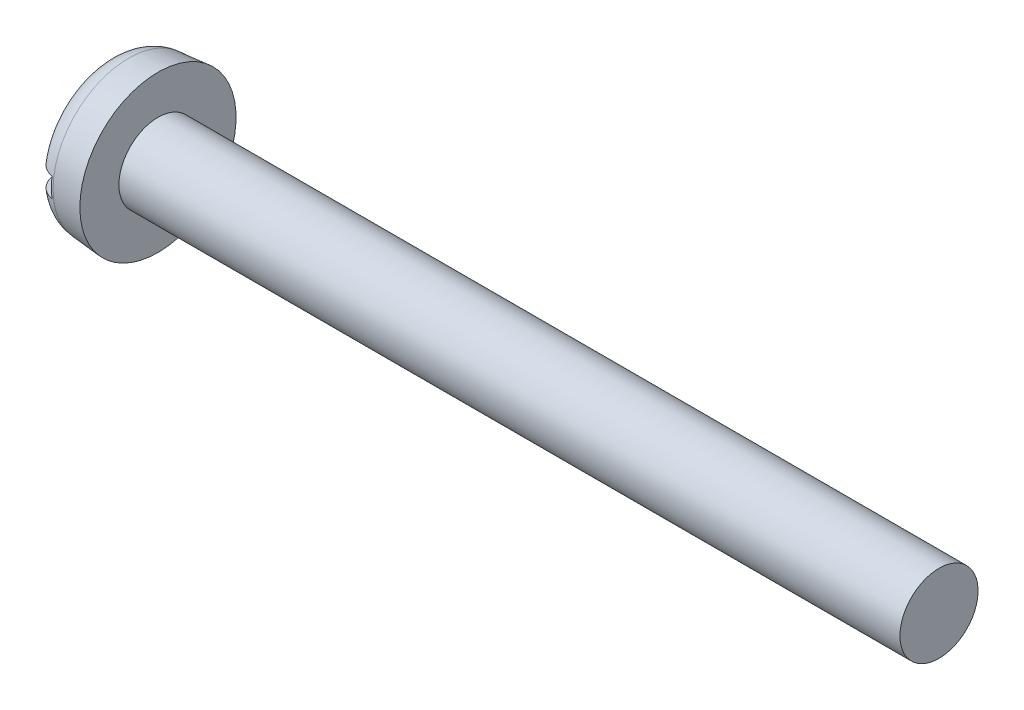
SolidWorks part; units mm, degrees
ref_plane "Plane1" through (0, 0, 0) normal (0, 0, 1) x (1, 0, 0)
ref_plane "Plane2" through (0, 0, 0) normal (0, 1, 0) x (1, 0, 0)
ref_plane "Plane3" through (0, 0, 0) normal (1, 0, 0) x (0, 0, -1)
sketch "BodySke" plane through (0, 0, 0) normal (0, 0, 1) x (1, 0, 0)
  line L0 (1.3, 1) -> (1.3, 2)
  line L1 (0, 0) -> (0, 1.8863)
  line L2 (-25.4, 0) -> (127, 0) construction
  line L3 (21.3, 0) -> (0, 0)
  line L4 (1.3, 1) -> (21.3, 1)
  line L5 (21.3, 1) -> (21.3, 0)
  line L6 (0, 1.8863) -> (1.3, 2)
  line L9 (1.7, 2.5875) -> (1.7, -6.9375) construction
  line L10 (1.3, 6.35) -> (1.3, -3.175) construction
  dimension "Length" = 20
  dimension "Head_ht" = 1.3
  dimension "Advance" = 0.4
  dimension "Thread_nom" = 20
  dimension "Head_dia" = 4
  dimension "Head_side_angle" = 5
  dimension "Diameter" = 2
revolve "Base-Revolve" add sketch "BodySke"
cosmetic thread "ThreadCosmetic" [suppressed]
fillet "Fillet1" [suppressed] radius 0.1
fillet "Fillet2" radius 0.6 1 edges at (0, 0, 1.8863)
sketch "Sketch2" plane through (0, 0, 0) normal (1, 0, 0) x (0, 0, -1)
  line L0 (2, -0.25) -> (-2, -0.25)
  line L1 (2, -0.25) -> (2, 0.25)
  line L2 (-2, 0.25) -> (2, 0.25)
  line L3 (-2, 0.25) -> (-2, -0.25)
  dimension "D1" = 4
  dimension "Slot_width" = 0.5
  dimension "D2" = 2
  dimension "D3" = 0.25
extrude "Slot" cut sketch "Sketch2" along normal blind 0.5
sketch "ThdSchSke" plane through (0, 0, 0) normal (0, 0, 1) x (1, 0, 0)
  line L0 (2.1, -0.774) -> (1.9418, -1)
  line L1 (2.1, -0.774) -> (2.2582, -1)
  line L2 (2.2582, -1) -> (2.2582, -1.25)
  line L3 (-3.175, 0) -> (5.1513, 0) construction
  line L5 (2.2582, -1.25) -> (1.9418, -1.25)
  line L6 (1.9418, -1.25) -> (1.9418, -1)
  dimension "Diameter" = 2
  dimension "SideAngle" = 55
  dimension "VeeAngle" = 70
  dimension "Thread_minor" = 1.548
  dimension "Overcut" = 2.5
  dimension "Start" = 2.1
revolve "ThreadSchematic" [suppressed] cut sketch "ThdSchSke" angle 360 about L3
pattern_linear "ThdSchPat" [suppressed]
equation "\"D1@Sketch2\" = \"Head_dia@BodySke\""
equation "\"D2@Sketch2\" = \"D1@Sketch2\" / 2"
equation "\"D3@Sketch2\" = \"Slot_width@Sketch2\" / 2"
equation "\"Thread_length@ThreadCosmetic\" = ((sgn( (\"Length@BodySke\" - \"Advance@BodySke\" * 2.0 ) - \"Thread_nom@BodySke\" )-1)*( (\"Length@BodySke\" - \"Advance@BodySke\"  * 2.0) - \"Thread_nom@BodySke\" ))/-2+ \"Thread_nom@BodySke\""
equation "\"Thread_minor@ThdSchSke\" = \"Thread_minor@ThreadCosmetic\""
equation "\"Diameter@ThdSchSke\" = \"Diameter@BodySke\""
equation "\"Overcut@ThdSchSke\" = \"Diameter@BodySke\" * 1.25"
equation "\"Start@ThdSchSke\" = \"Head_ht@BodySke\" + \"Length@BodySke\" - \"Thread_length@ThreadCosmetic\"  '---Non-countersunk---"
equation "\"Num_threads@ThdSchPat\" = int( \"Thread_length@ThreadCosmetic\" / \"Advance@BodySke\" + 0.999 )  + 1"
equation "\"Advance@ThdSchPat\" = \"Thread_length@ThreadCosmetic\" /  (\"Num_threads@ThdSchPat\" - 1) 'relax it"
